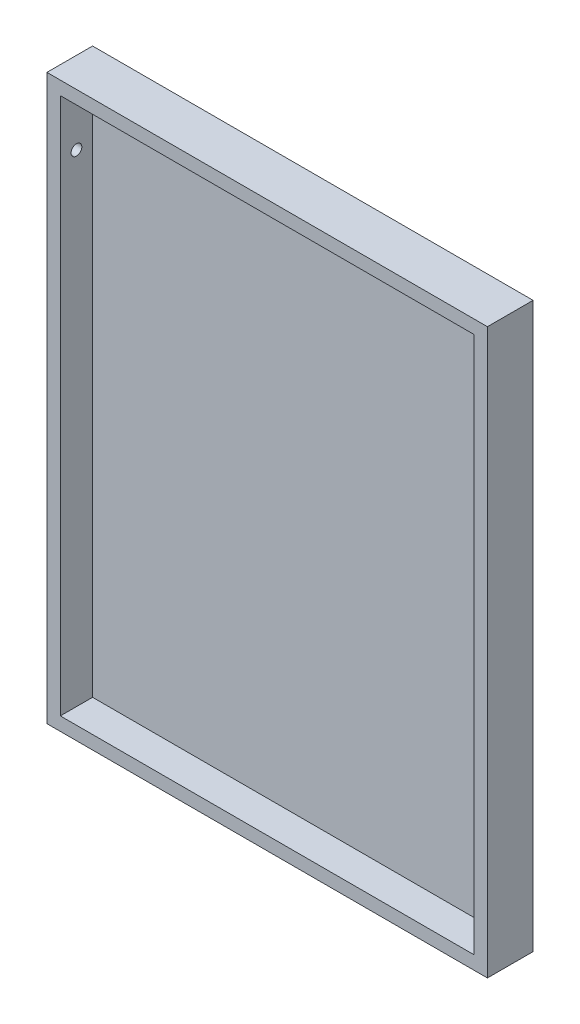
SolidWorks part; units mm, degrees
ref_plane "Front Plane" through (0, 0, 0) normal (1, 0, 0) x (0, 1, 0)
ref_plane "Top Plane" through (0, 0, 0) normal (0, 0, 1) x (0, 1, 0)
ref_plane "Right Plane" through (0, 0, 0) normal (0, 1, 0) x (-1, 0, 0)
sketch "Sketch1" plane through (0, 0, 0) normal (0, 0, 1) x (0, 1, 0)
  line L1 (-100, 77) -> (100, 77) construction
  line L2 (-100, 77) -> (-100, -77) construction
  line L3 (-100, -77) -> (100, -77) construction
  line L4 (100, 77) -> (100, -77) construction
  line L5 (-100, 77) -> (100, -77) construction
  line L6 (-100, -77) -> (100, 77) construction
  line L7 (-105, 82) -> (105, 82)
  line L8 (-105, 82) -> (-105, -82)
  line L9 (-105, -82) -> (105, -82)
  line L10 (105, 82) -> (105, -82)
  line L11 (-105, 82) -> (105, -82) construction
  line L12 (-105, -82) -> (105, 82) construction
  point P0 (0, 0)
  point P6 (0, 0)
  dimension "D1" = 200
  dimension "D2" = 154
  dimension "D3" = 5
  dimension "D4" = 5
extrude "Boss-Extrude1" add sketch "Sketch1" along normal blind 5
sketch "Sketch2" plane through (0, 0, 5) normal (0, 0, 1) x (1, 0, 0)
  line L0 (-82, 105) -> (-82, -105) construction
  line L1 (-77, 100) -> (77, 100)
  line L2 (-77, 100) -> (-77, -100)
  line L3 (-77, -100) -> (77, -100)
  line L4 (77, 100) -> (77, -100)
  line L5 (-77, 100) -> (77, -100) construction
  line L6 (-77, -100) -> (77, 100) construction
  line L7 (82, 105) -> (-82, 105) construction
  line L9 (-82, 105) -> (82, 105)
  line L10 (-82, 105) -> (-82, -105)
  line L11 (-82, -105) -> (82, -105)
  line L12 (82, 105) -> (82, -105)
  line L13 (-82, 105) -> (82, -105) construction
  line L14 (-82, -105) -> (82, 105) construction
  point P0 (0, 0)
  point P10 (0, 0)
  dimension "D1" = 5
  dimension "D2" = 5
extrude "Boss-Extrude2" add sketch "Sketch2" along normal blind 12
sketch "Sketch3" plane through (77, 0, 0) normal (-1, 0, 0) x (0, -1, 0)
  line L0 (-79.5, 13) -> (-79.5, 17) construction
  line L1 (100, 17) -> (-100, 17) construction
  line L2 (-79.5, 9) -> (-79.5, 5) construction
  line L3 (100, 5) -> (-100, 5) construction
  line L4 (-100, 17) -> (-100, 5) construction
  circle A0 centre (-79.5, 11) radius 2
  dimension "D1" = 4
  dimension "D2" = 20.5
extrude "Cut-Extrude1" cut sketch "Sketch3" along normal up to surface (159 mm away) contours A0 up to face at (-82, 0, 8.5)
